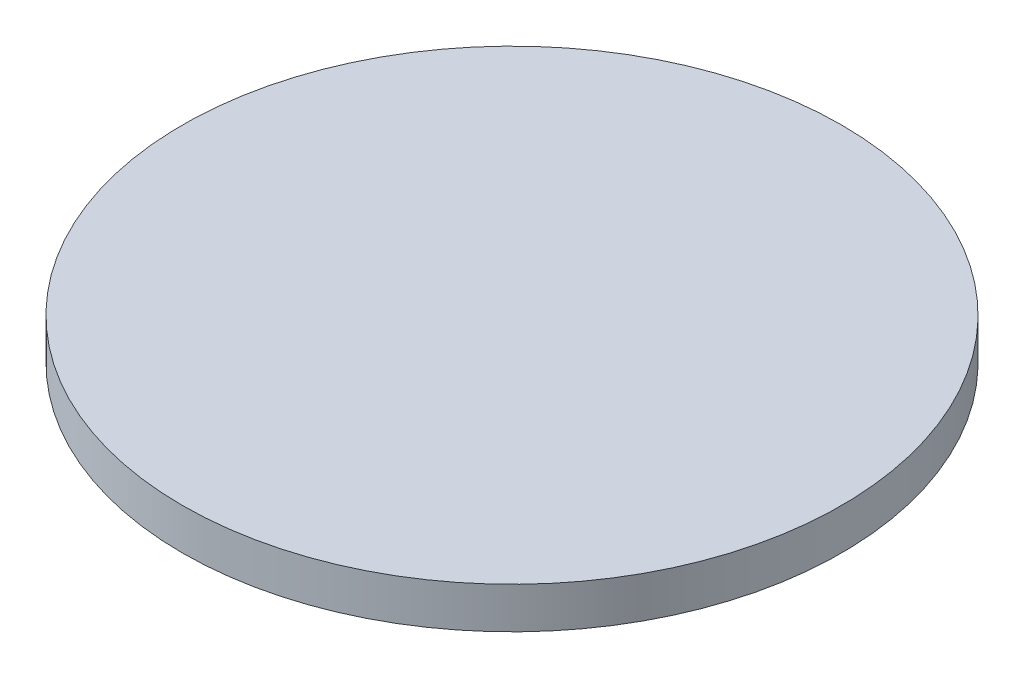
SolidWorks part; units mm, degrees
ref_plane "Front Plane" through (0, 0, 0) normal (0, 0, 1) x (1, 0, 0)
ref_plane "Top Plane" through (0, 0, 0) normal (0, 1, 0) x (1, 0, 0)
ref_plane "Right Plane" through (0, 0, 0) normal (1, 0, 0) x (0, 0, -1)
other "Configuration Table"
sketch "Sketch1" plane through (0, 0, 0) normal (0, 1, 0) x (1, 0, 0)
  circle A0 centre (185, 300) radius 160
extrude "PRESS_poset_kelepcesi_D320" add sketch "Sketch1" along normal blind 20 from offset 1770 separate body
